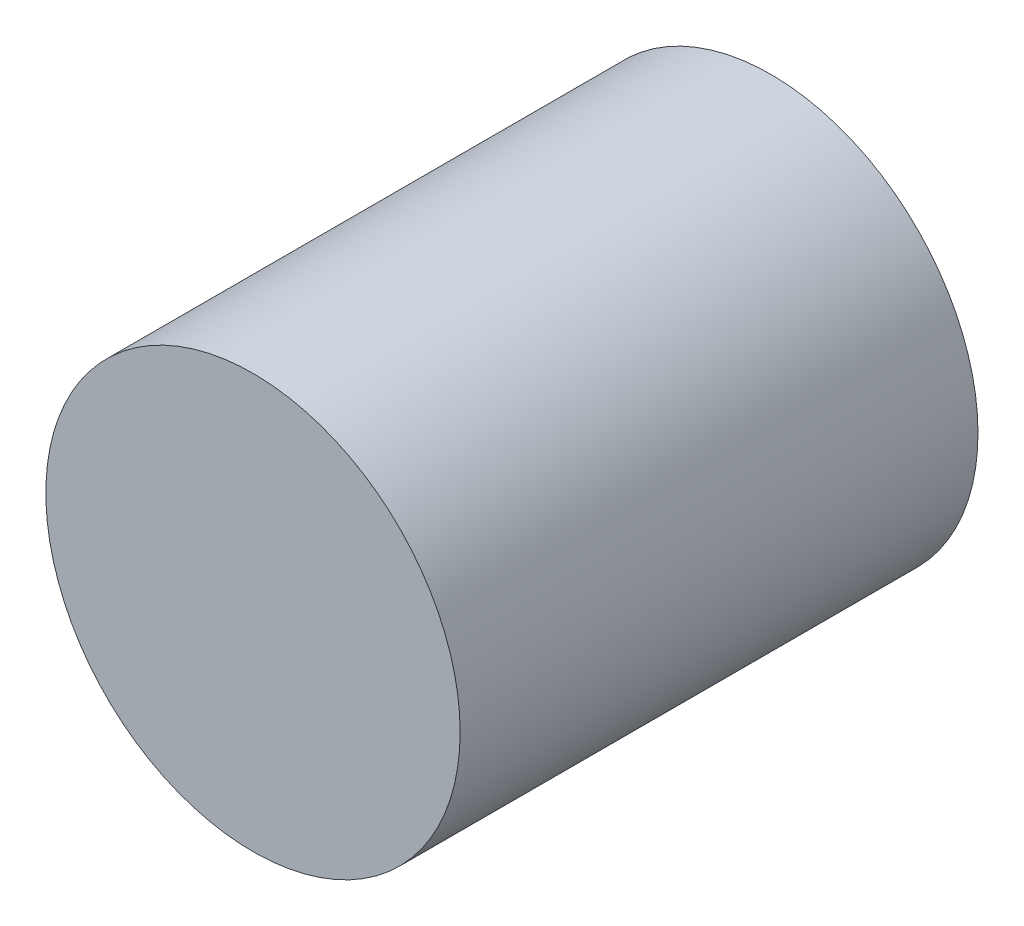
SolidWorks part; units mm, degrees
ref_plane "Спереди" through (0, 0, 0) normal (0, 0, 1) x (1, 0, 0)
ref_plane "Сверху" through (0, 0, 0) normal (0, 1, 0) x (1, 0, 0)
ref_plane "Справа" through (0, 0, 0) normal (1, 0, 0) x (0, 0, -1)
sketch "Эскиз1" plane through (0, 0, 0) normal (0, 0, 1) x (1, 0, 0)
  circle A0 centre (0, 0) radius 2
  dimension "D1" = 4
extrude "Бобышка-Вытянуть1" add sketch "Эскиз1" along normal blind 5
